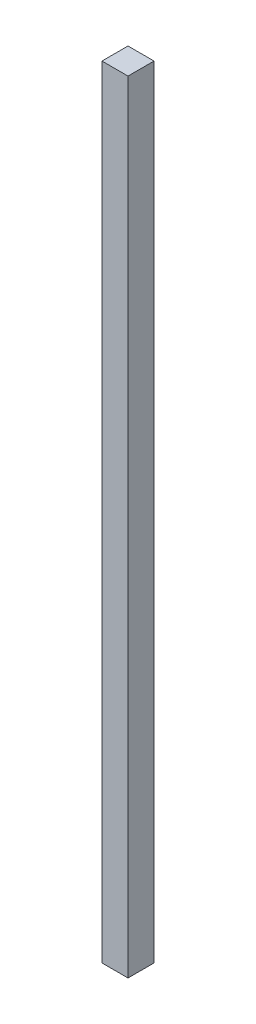
SolidWorks part; units mm, degrees
material "Oak"
ref_plane "Front Plane" through (0, 0, 0) normal (0, 0, 1) x (1, 0, 0)
ref_plane "Top Plane" through (0, 0, 0) normal (0, 1, 0) x (1, 0, 0)
ref_plane "Right Plane" through (0, 0, 0) normal (1, 0, 0) x (0, 0, -1)
other "Configuration Table"
sketch "Sketch1" plane through (0, 0, 0) normal (0, 1, 0) x (1, 0, 0)
  line L1 (-25, -25) -> (25, -25)
  line L2 (-25, -25) -> (-25, 25)
  line L3 (-25, 25) -> (25, 25)
  line L4 (25, -25) -> (25, 25)
  line L5 (-25, -25) -> (25, 25) construction
  line L6 (-25, 25) -> (25, -25) construction
  point P0 (0, 0)
  dimension "D1" = 50
extrude "Boss-Extrude1" add sketch "Sketch1" along normal blind 1500
sketch "Sketch2" [suppressed] plane through (0, 0, -25) normal (0, 0, -1) x (-1, 0, 0)
  line L0 (10, 0) -> (-25, 0) construction
  line L1 (-10, 0) -> (10, 0)
  line L2 (-10, 0) -> (-10, 2500)
  line L3 (-10, 2500) -> (10, 2500)
  line L4 (10, 0) -> (10, 2500)
  line L5 (-25, 2500) -> (-25, 0) construction
  line L6 (-10, 0) -> (25, 0) construction
  line L7 (25, 2500) -> (25, 0) construction
  line L8 (25, 2500) -> (-1975, 2500) construction
  line L9 (-25, 0) -> (25, 0) construction
  dimension "D1" = 20
extrude "Cut-Extrude1" [suppressed] cut sketch "Sketch2" against normal blind 25
